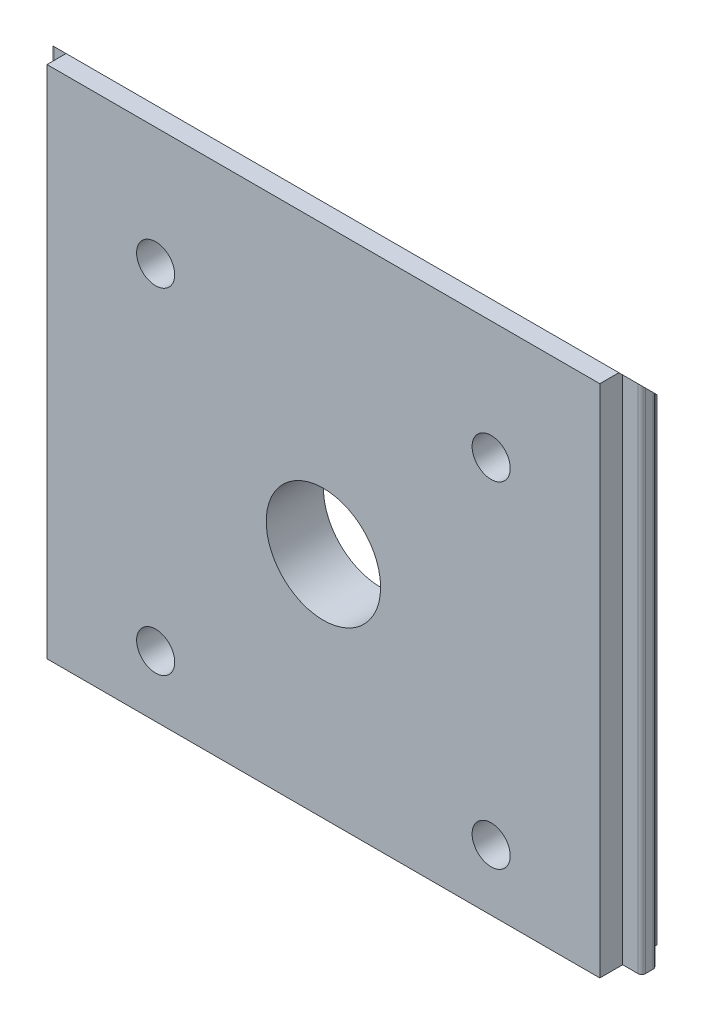
SolidWorks part; units mm, degrees
ref_plane "Front Plane" through (0, 0, 0) normal (0, 0, 1) x (1, 0, 0)
ref_plane "Top Plane" through (0, 0, 0) normal (0, 1, 0) x (1, 0, 0)
ref_plane "Right Plane" through (0, 0, 0) normal (1, 0, 0) x (0, 0, -1)
sketch "Sketch1" plane through (0, 0, 0) normal (0, 0, 1) x (1, 0, 0)
  line L1 (18.415, -17.145) -> (-18.415, -17.145)
  line L2 (18.415, -17.145) -> (18.415, 17.145)
  line L3 (18.415, 17.145) -> (-18.415, 17.145)
  line L4 (-18.415, -17.145) -> (-18.415, 17.145)
  line L5 (18.415, -17.145) -> (-18.415, 17.145) construction
  line L6 (18.415, 17.145) -> (-18.415, -17.145) construction
  point P0 (0, 0)
  dimension "D1" = 34.29
  dimension "D2" = 36.83
extrude "Boss-Extrude1" add sketch "Sketch1" along normal blind 3.81
sketch "Sketch2" plane through (18.415, 0, 0) normal (1, 0, 0) x (0, 0, -1)
  line L0 (-3.81, 17.145) -> (0, 17.145) construction
  line L1 (-2.286, 17.145) -> (-1.27, 17.145)
  line L2 (-2.286, 17.145) -> (-2.286, -17.145)
  line L3 (-2.286, -17.145) -> (-1.27, -17.145)
  line L4 (-1.27, 17.145) -> (-1.27, -17.145)
  line L5 (-3.81, -17.145) -> (0, -17.145) construction
  line L6 (0, -17.145) -> (0, 17.145) construction
  dimension "D1" = 1.016
  dimension "D2" = 1.27
extrude "Boss-Extrude2" add sketch "Sketch2" along normal blind 1.27
mirror "Mirror1" about plane through (0, 0, 0) normal (1, 0, 0) of "Boss-Extrude2"
fillet "Fillet1" radius 0.254 4 edges at (-19.685, 0, 2.286) (19.685, 0, 2.286) (19.685, 0, 1.27) (-19.685, 0, 1.27)
sketch "Sketch3" plane through (0, 0, 3.81) normal (0, 0, 1) x (1, 0, 0)
  line L0 (18.415, 17.145) -> (-18.415, 17.145) construction
  line L2 (11.176, -13.081) -> (-11.176, -13.081) construction
  line L3 (11.176, -13.081) -> (11.176, 9.271) construction
  line L4 (11.176, 9.271) -> (-11.176, 9.271) construction
  line L5 (-11.176, -13.081) -> (-11.176, 9.271) construction
  line L6 (11.176, -13.081) -> (-11.176, 9.271) construction
  line L7 (11.176, 9.271) -> (-11.176, -13.081) construction
  circle A0 centre (0, -1.905) radius 3.81
  circle A1 centre (-11.176, 9.271) radius 1.27
  circle A2 centre (11.176, 9.271) radius 1.27
  circle A3 centre (11.176, -13.081) radius 1.27
  circle A4 centre (-11.176, -13.081) radius 1.27
  dimension "D2" = 7.62
  dimension "D4" = 2.54
  dimension "D1" = 19.05
  dimension "D3" = 22.352
extrude "Cut-Extrude1" cut sketch "Sketch3" against normal blind 3.81
chamfer "Chamfer1" distance 2.54 angle 45 1 edges at (0, 17.145, 0)
